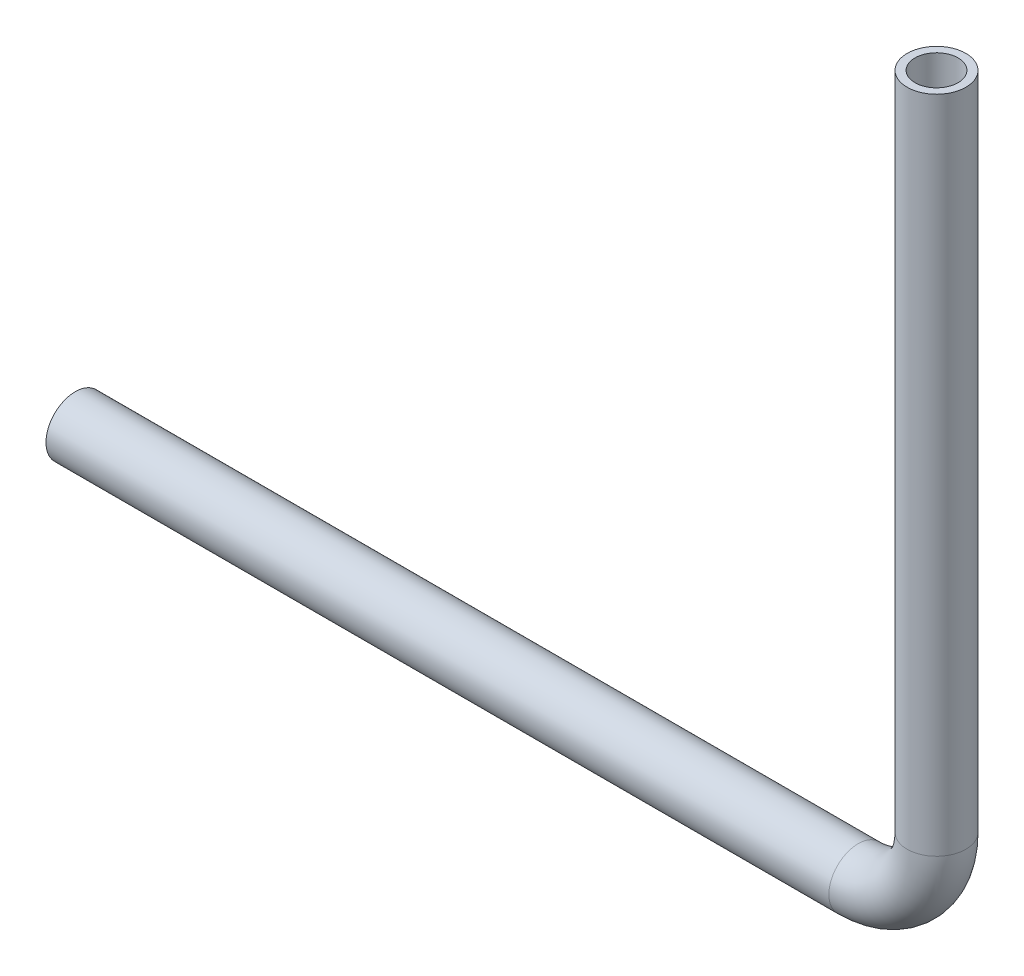
SolidWorks part; units mm, degrees
ref_plane "Front Plane" through (0, 0, 0) normal (0, 0, 1) x (1, 0, 0)
ref_plane "Top Plane" through (0, 0, 0) normal (0, 1, 0) x (1, 0, 0)
ref_plane "Right Plane" through (0, 0, 0) normal (1, 0, 0) x (0, 0, -1)
sketch "Sketch5" plane through (0, 0, 0) normal (0, 0, 1) x (1, 0, 0)
  line L0 (-136.7218, 77.0529) -> (63.2782, 77.0529)
  line L1 (83.2782, 97.0529) -> (83.2782, 265.6369)
  arc A0 (63.2782, 77.0529) -> (83.2782, 97.0529) centre (63.2782, 97.0529) ccw
  dimension "D4" = 20
  dimension "D1" = 200
  dimension "D5" = 168.5841
  dimension "D2" = 90
  dimension "D3" = 31.4159
ref_plane "Plane1" through (-136.7218, 0, 0) normal (1, 0, 0) x (0, 0, -1)
sketch "Sketch6" plane through (-136.7218, 0, 0) normal (1, 0, 0) x (0, 0, -1)
  circle A0 centre (0, 77.0529) radius 5.5
  circle A1 centre (0, 77.0529) radius 7.5
  dimension "D1" = 15
  dimension "D2" = 2
sweep "Sweep1" add profiles "Sketch6" path "Sketch5"
equation "\"a\"= \"D3@Sketch5\""
equation "\"D5@Sketch5\"= abs ( 200 - \"a\" )"
